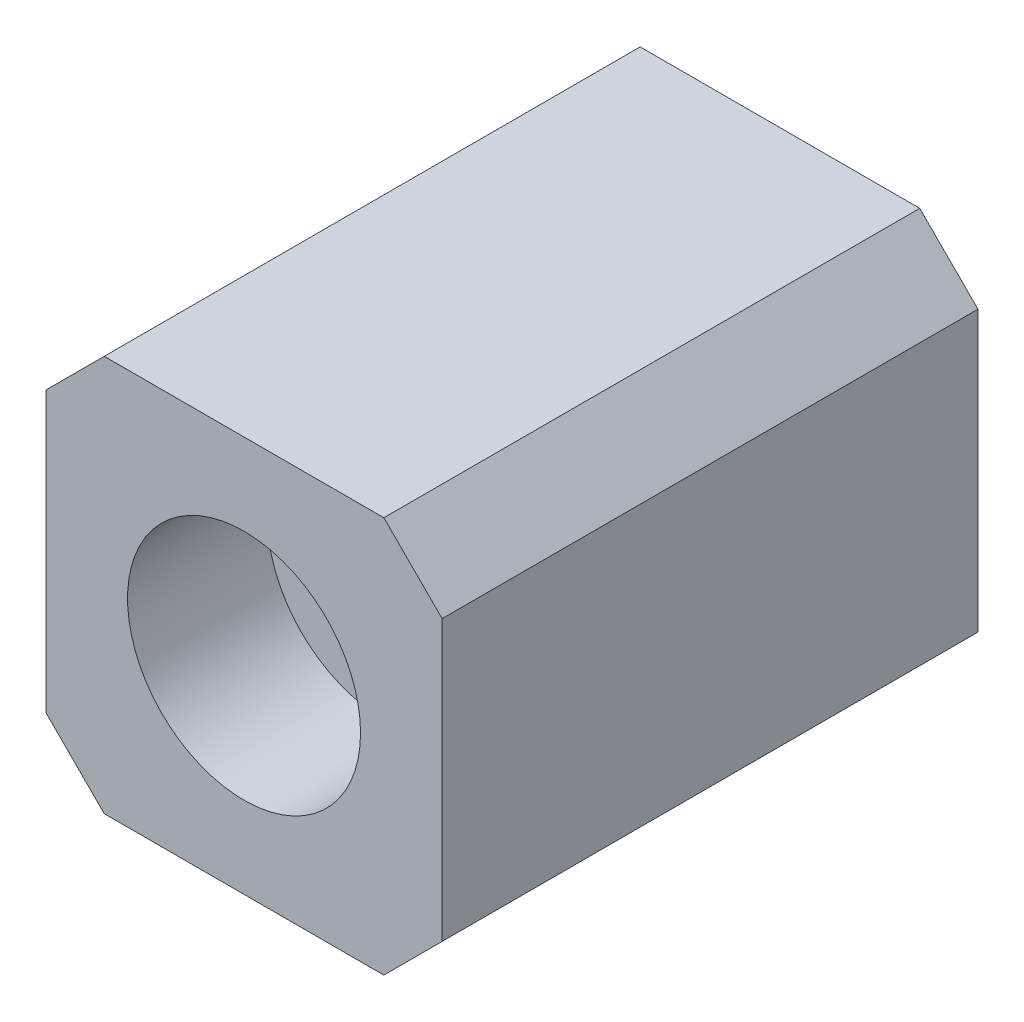
SolidWorks part; units mm, degrees
ref_plane "Front Plane" through (0, 0, 0) normal (0, 0, 1) x (1, 0, 0)
ref_plane "Top Plane" through (0, 0, 0) normal (0, 1, 0) x (1, 0, 0)
ref_plane "Right Plane" through (0, 0, 0) normal (1, 0, 0) x (0, 0, -1)
sketch "Sketch3" plane through (0, 0, 0) normal (0, 0, 1) x (1, 0, 0)
  line L0 (0, 0) -> (17, 0)
  line L1 (17, 0) -> (17, -17)
  line L2 (17, -17) -> (0, -17)
  line L3 (0, -17) -> (0, 0)
  dimension "D1" = 17
  dimension "D2" = 17
extrude "Boss-Extrude1" add sketch "Sketch3" along normal blind 23
sketch "Sketch4" plane through (0, 0, 23) normal (0, 0, 1) x (1, 0, 0)
  line L0 (2.5, 0) -> (0, -2.5)
  line L1 (17, 0) -> (0, 0) construction
  line L2 (0, 0) -> (0, -17) construction
  line L3 (8.5, 0) -> (8.5, -17) construction
  line L4 (0, -17) -> (17, -17) construction
  line L5 (0, -8.5) -> (17, -8.5) construction
  line L6 (17, -17) -> (17, 0) construction
  line L7 (14.5, 0) -> (17, -2.5)
  line L8 (14.5, -17) -> (17, -14.5)
  line L9 (2.5, -17) -> (0, -14.5)
  line M6 (17, -17) -> (17, 0)
  line M7 (17, 0) -> (0, 0)
  line M8 (0, 0) -> (0, -17)
  line M9 (0, -17) -> (17, -17)
  dimension "D1" = 2.5
  dimension "D2" = 2.5
extrude "Cut-Extrude1" cut sketch "Sketch4" against normal through all contours L7 M7 M6 | L0 M7 M8 | L9 M9 M8 | L8 M9 M6
sketch "Sketch5" plane through (0, 0, 23) normal (0, 0, 1) x (1, 0, 0)
  line L0 (8.5, 0) -> (8.5, -17) construction
  line L1 (14.5, 0) -> (2.5, 0) construction
  line L2 (2.5, -17) -> (14.5, -17) construction
  line L3 (0, -8.5) -> (17, -8.5) construction
  line L4 (0, -2.5) -> (0, -14.5) construction
  line L5 (17, -14.5) -> (17, -2.5) construction
  circle A0 centre (8.5, -8.5) radius 5
  dimension "D1" = 10
extrude "Cut-Extrude2" cut sketch "Sketch5" against normal blind 6
sketch "Sketch6" plane through (0, 0, 0) normal (0, 0, -1) x (-1, 0, 0)
  line L0 (-17, -8.5) -> (0, -8.5) construction
  line L1 (-17, -14.5) -> (-17, -2.5) construction
  line L2 (0, -2.5) -> (0, -14.5) construction
  line L3 (-8.5, 0) -> (-8.5, -17) construction
  line L4 (-14.5, 0) -> (-2.5, 0) construction
  line L5 (-2.5, -17) -> (-14.5, -17) construction
  line L6 (-10.55, -6.9834) -> (-10.55, -10.0166)
  arc A0 (-10.55, -10.0166) -> (-10.55, -6.9834) centre (-8.5, -8.5) ccw
  dimension "D1" = 5.1
  dimension "D2" = 2.05
extrude "Cut-Extrude3" cut sketch "Sketch6" against normal blind 6
